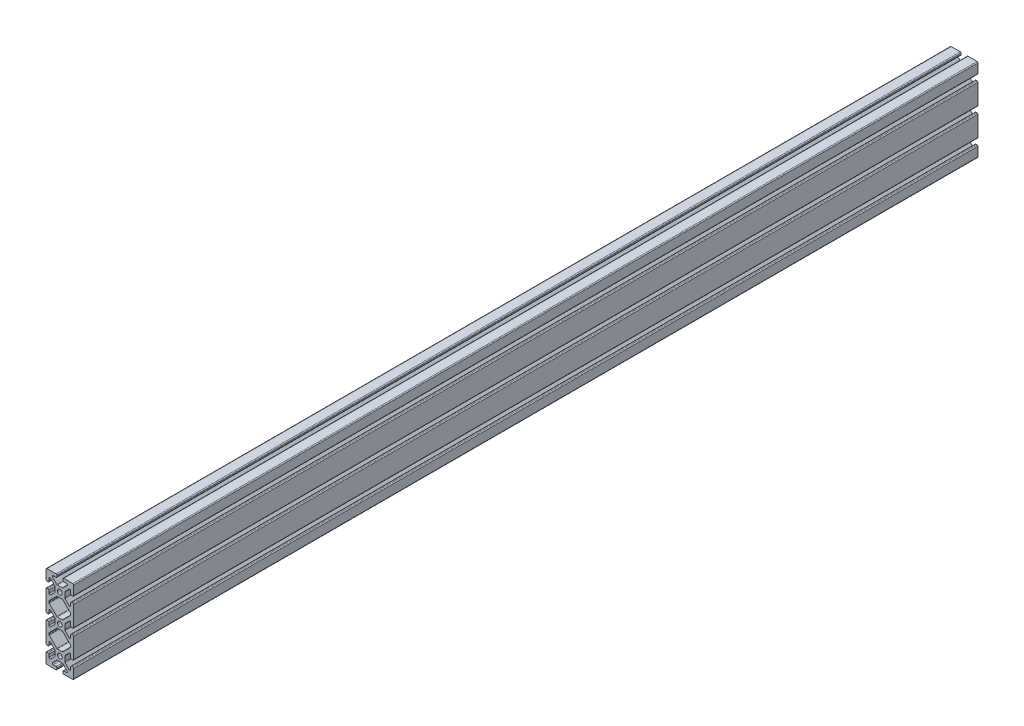
SolidWorks part; units mm, degrees
material "6061 Alloy"
ref_plane "Front Plane" through (0, 0, 0) normal (0, 0, 1) x (1, 0, 0)
ref_plane "Top Plane" through (0, 0, 0) normal (0, 1, 0) x (1, 0, 0)
ref_plane "Right Plane" through (0, 0, 0) normal (1, 0, 0) x (0, 0, -1)
sketch "Sketch1" plane through (0, 0, 0) normal (0, 0, 1) x (1, 0, 0)
  line L0 (0, 0) -> (0, 50000) construction
  line L1 (-19.05, 19.05) -> (19.05, 19.05) construction
  line L2 (-19.05, 19.05) -> (-19.05, -19.05) construction
  line L3 (-19.05, -19.05) -> (19.05, -19.05) construction
  line L4 (19.05, 19.05) -> (19.05, -19.05) construction
  line L5 (-19.05, 19.05) -> (19.05, -19.05) construction
  line L6 (-19.05, -19.05) -> (19.05, 19.05) construction
  line L7 (0, 0) -> (50000, 0) construction
  line L8 (-12.1123, 14.986) -> (-3.8827, 6.7564)
  line L9 (-19.05, 19.05) -> (-4.064, 19.05)
  line L10 (-4.064, 19.05) -> (-4.064, 14.986)
  line L11 (-4.064, 14.986) -> (-12.1123, 14.986)
  line L12 (-3.8827, 6.7564) -> (3.8827, 6.7564)
  line L13 (-6.7564, 3.8827) -> (-6.7564, -3.8827)
  line L14 (-14.986, 12.1123) -> (-6.7564, 3.8827)
  line L15 (-14.986, 4.064) -> (-14.986, 12.1123)
  line L16 (-19.05, 4.064) -> (-14.986, 4.064)
  line L17 (-19.05, 19.05) -> (-19.05, 4.064)
  line L18 (19.05, 4.064) -> (14.986, 4.064)
  line L19 (19.05, 19.05) -> (19.05, 4.064)
  line L20 (14.986, 4.064) -> (14.986, 12.1123)
  line L21 (14.986, 12.1123) -> (6.7564, 3.8827)
  line L22 (6.7564, 3.8827) -> (6.7564, -3.8827)
  line L23 (12.1123, 14.986) -> (3.8827, 6.7564)
  line L24 (4.064, 14.986) -> (12.1123, 14.986)
  line L25 (4.064, 19.05) -> (4.064, 14.986)
  line L26 (19.05, 19.05) -> (4.064, 19.05)
  line L27 (14.986, -12.1123) -> (6.7564, -3.8827)
  line L28 (14.986, -4.064) -> (14.986, -12.1123)
  line L29 (19.05, -4.064) -> (14.986, -4.064)
  line L30 (19.05, -34.036) -> (19.05, -4.064)
  line L31 (-19.05, -34.036) -> (-14.986, -34.036)
  line L32 (-3.8827, -6.7564) -> (-14.986, -17.8597)
  line L33 (-14.986, -34.036) -> (-14.986, -25.9877)
  line L34 (3.8827, -6.7564) -> (14.986, -17.8597)
  line L35 (-3.8827, -6.7564) -> (3.8827, -6.7564)
  line L36 (-14.986, -25.9877) -> (-6.7564, -34.2173)
  line L37 (-3.8827, -31.3436) -> (3.8827, -31.3436)
  line L38 (3.8827, -31.3436) -> (14.986, -20.2403)
  line L39 (-3.8827, -31.3436) -> (-14.986, -20.2403)
  line L40 (-14.986, -12.1123) -> (-6.7564, -3.8827)
  line L41 (-14.986, -4.064) -> (-14.986, -12.1123)
  line L42 (-19.05, -4.064) -> (-14.986, -4.064)
  line L43 (-19.05, -34.036) -> (-19.05, -4.064)
  line L44 (19.05, -34.036) -> (14.986, -34.036)
  line L45 (14.986, -34.036) -> (14.986, -25.9877)
  line L46 (14.986, -25.9877) -> (6.7564, -34.2173)
  line L47 (14.986, -58.3403) -> (14.986, -55.9597)
  line L48 (-14.986, -58.3403) -> (-14.986, -55.9597)
  line L49 (14.986, -50.2123) -> (6.7564, -41.9827)
  line L50 (14.986, -42.164) -> (14.986, -50.2123)
  line L51 (6.7564, -41.9827) -> (6.7564, -34.2173)
  line L52 (19.05, -42.164) -> (14.986, -42.164)
  line L53 (-19.05, -42.164) -> (-19.05, -72.136)
  line L54 (-19.05, -72.136) -> (-14.986, -72.136)
  line L55 (-14.986, -72.136) -> (-14.986, -64.0877)
  line L56 (-14.986, -64.0877) -> (-6.7564, -72.3173)
  line L57 (-3.8827, -44.8564) -> (-14.986, -55.9597)
  line L58 (3.8827, -44.8564) -> (14.986, -55.9597)
  line L59 (-3.8827, -44.8564) -> (3.8827, -44.8564)
  line L60 (-6.7564, -41.9827) -> (-6.7564, -34.2173)
  line L61 (-14.986, -50.2123) -> (-6.7564, -41.9827)
  line L62 (-3.8827, -69.4436) -> (3.8827, -69.4436)
  line L63 (3.8827, -69.4436) -> (14.986, -58.3403)
  line L64 (-14.986, -42.164) -> (-14.986, -50.2123)
  line L65 (-3.8827, -69.4436) -> (-14.986, -58.3403)
  line L66 (-14.986, -17.8597) -> (-14.986, -20.2403)
  line L67 (14.986, -17.8597) -> (14.986, -20.2403)
  line L68 (0, -38.1) -> (-50000, -38.1) construction
  line L69 (-19.05, -42.164) -> (-14.986, -42.164)
  line L70 (19.05, -42.164) -> (19.05, -72.136)
  line L71 (19.05, -72.136) -> (14.986, -72.136)
  line L72 (14.986, -72.136) -> (14.986, -64.0877)
  line L73 (14.986, -64.0877) -> (6.7564, -72.3173)
  line L74 (19.05, -95.25) -> (4.064, -95.25)
  line L75 (4.064, -95.25) -> (4.064, -91.186)
  line L76 (4.064, -91.186) -> (12.1123, -91.186)
  line L77 (12.1123, -91.186) -> (3.8827, -82.9564)
  line L78 (6.7564, -80.0827) -> (6.7564, -72.3173)
  line L79 (14.986, -88.3123) -> (6.7564, -80.0827)
  line L80 (14.986, -80.264) -> (14.986, -88.3123)
  line L81 (19.05, -95.25) -> (19.05, -80.264)
  line L82 (19.05, -80.264) -> (14.986, -80.264)
  line L83 (-19.05, -95.25) -> (-19.05, -80.264)
  line L84 (-19.05, -80.264) -> (-14.986, -80.264)
  line L85 (-14.986, -80.264) -> (-14.986, -88.3123)
  line L86 (-14.986, -88.3123) -> (-6.7564, -80.0827)
  line L87 (-6.7564, -80.0827) -> (-6.7564, -72.3173)
  line L88 (-3.8827, -82.9564) -> (3.8827, -82.9564)
  line L89 (-4.064, -91.186) -> (-12.1123, -91.186)
  line L90 (-4.064, -95.25) -> (-4.064, -91.186)
  line L91 (-19.05, -95.25) -> (-4.064, -95.25)
  line L92 (-12.1123, -91.186) -> (-3.8827, -82.9564)
  circle A0 centre (0, 0) radius 3.3274
  circle A1 centre (0, -38.1) radius 3.3274
  circle A2 centre (0, -76.2) radius 3.3274
  point P0 (0, 0)
  point P28 (0, 6.7564)
  point P32 (6.7564, 0)
  point P44 (-6.7564, 0)
  point P64 (-6.7564, -38.1)
  point P65 (6.7564, -38.1)
  point P74 (-6.7564, -38.1)
  point P75 (6.7564, -38.1)
  point P107 (-6.7564, -76.2)
  point P108 (6.7564, -76.2)
  point P109 (0, -82.9564)
  dimension "D3" = 14.986
  dimension "D2" = 6.6548
  dimension "D1" = 38.1
  dimension "D4" = 4.064
  dimension "D5" = 2.032
  dimension "D6" = 12.2936
extrude "Boss-Extrude1" add sketch "Sketch1" along normal blind 1244.6
fillet "Fillet1" radius 1.27 84 edges at (-14.986, -34.036, 622.3) (-19.05, -34.036, 622.3) (-6.7564, -34.2173, 622.3) (6.7564, -34.2173, 622.3) (14.986, -25.9877, 622.3) (14.986, -34.036, 622.3) (19.05, -34.036, 622.3) (-19.05, 4.064, 622.3) (-14.986, 4.064, 622.3) (-14.986, 12.1123, 622.3) (-6.7564, 3.8827, 622.3) (-6.7564, -3.8827, 622.3) (-19.05, -4.064, 622.3) (-14.986, -4.064, 622.3) (-14.986, -12.1123, 622.3) (3.8827, -31.3436, 622.3) (-3.8827, -31.3436, 622.3) (-3.8827, -6.7564, 622.3) (3.8827, -6.7564, 622.3) (14.986, -12.1123, 622.3) (19.05, -4.064, 622.3) (14.986, -4.064, 622.3) (6.7564, -3.8827, 622.3) (6.7564, 3.8827, 622.3) (14.986, 4.064, 622.3) (19.05, 4.064, 622.3) (14.986, 12.1123, 622.3) (19.05, 19.05, 622.3) (4.064, 19.05, 622.3) (4.064, 14.986, 622.3) (12.1123, 14.986, 622.3) (3.8827, 6.7564, 622.3) (-3.8827, 6.7564, 622.3) (-12.1123, 14.986, 622.3) (-4.064, 14.986, 622.3) (-4.064, 19.05, 622.3) (-19.05, 19.05, 622.3) (14.986, -20.2403, 622.3) (14.986, -17.8597, 622.3) (-14.986, -20.2403, 622.3) (-14.986, -17.8597, 622.3) (-14.986, -88.3123, 622.3) (-19.05, -95.25, 622.3) (-4.064, -95.25, 622.3) (-4.064, -91.186, 622.3) (-12.1123, -91.186, 622.3) (-3.8827, -82.9564, 622.3) (3.8827, -82.9564, 622.3) (12.1123, -91.186, 622.3) (4.064, -91.186, 622.3) (4.064, -95.25, 622.3) (19.05, -95.25, 622.3) (19.05, -80.264, 622.3) (14.986, -80.264, 622.3) (14.986, -88.3123, 622.3) (-19.05, -72.136, 622.3) (-14.986, -72.136, 622.3) (14.986, -72.136, 622.3) (19.05, -72.136, 622.3) (-19.05, -80.264, 622.3) (-14.986, -80.264, 622.3) (-6.7564, -80.0827, 622.3) (6.7564, -80.0827, 622.3) (-6.7564, -72.3173, 622.3) (6.7564, -72.3173, 622.3) (3.8827, -69.4436, 622.3) (-3.8827, -69.4436, 622.3) (3.8827, -44.8564, 622.3) (-3.8827, -44.8564, 622.3) (-14.986, -64.0877, 622.3) (14.986, -64.0877, 622.3) (14.986, -58.3403, 622.3) (14.986, -55.9597, 622.3) (-14.986, -58.3403, 622.3) (-14.986, -55.9597, 622.3) (-19.05, -42.164, 622.3) (-14.986, -42.164, 622.3) (14.986, -50.2123, 622.3) (-14.986, -50.2123, 622.3) (19.05, -42.164, 622.3) (14.986, -42.164, 622.3) (6.7564, -41.9827, 622.3) (-6.7564, -41.9827, 622.3) (-14.986, -25.9877, 622.3)
